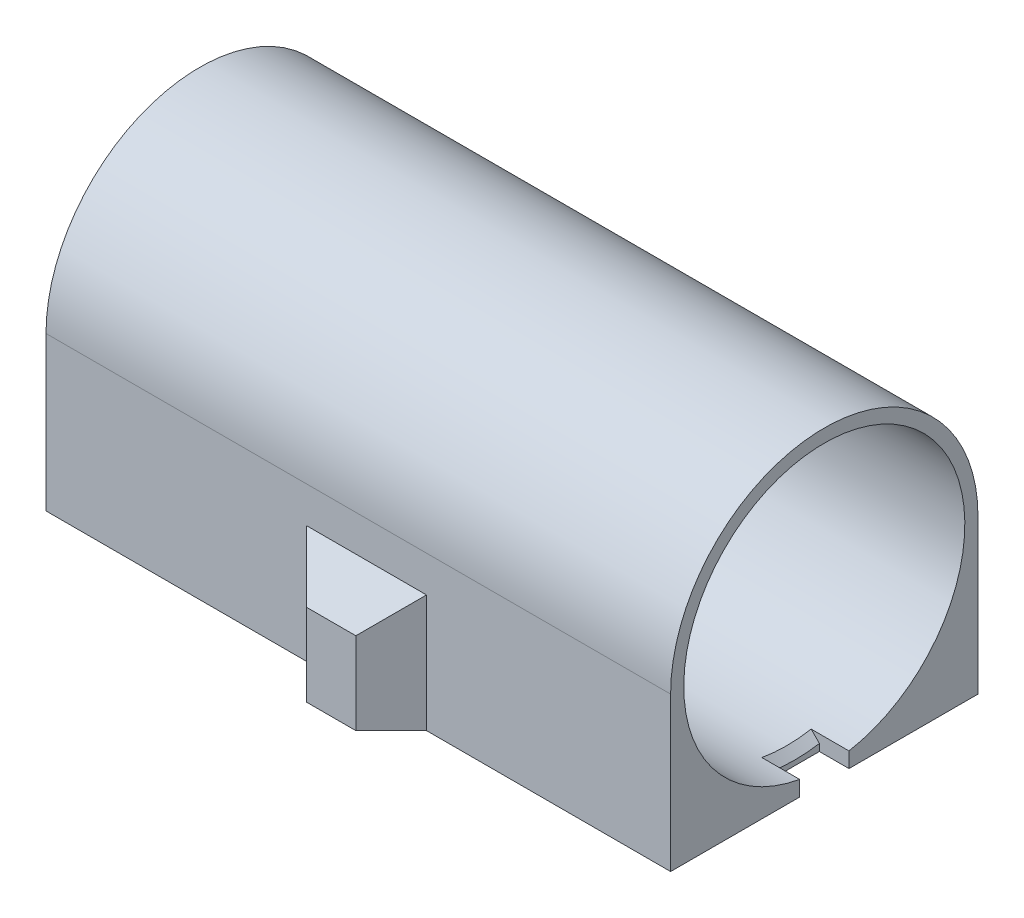
SolidWorks part; units mm, degrees
ref_plane "Спереди" through (0, 0, 0) normal (0, 0, 1) x (1, 0, 0)
ref_plane "Сверху" through (0, 0, 0) normal (0, 1, 0) x (1, 0, 0)
ref_plane "Справа" through (0, 0, 0) normal (1, 0, 0) x (0, 0, -1)
sketch "Эскиз1" plane through (0, 0, 0) normal (1, 0, 0) x (0, 0, -1)
  line L0 (-9.35, 0) -> (-9.35, -9.35)
  line L1 (-9.35, -9.35) -> (9.35, -9.35)
  line L2 (0, -1000) -> (0, 49000) construction
  line L3 (9.35, 0) -> (9.35, -9.35)
  arc A3 (9.35, 0) -> (-9.35, 0) centre (0, 0) ccw
  circle A4 centre (0, 0) radius 8.35 construction
  circle A5 centre (0, 0) radius 8.55
  arc A6 (0, -9.35) -> (9.35, 0) centre (0, 0) ccw construction
  circle A7 centre (0, 0) radius 9.35 construction
  arc A8 (-9.35, 0) -> (0, -9.35) centre (0, 0) ccw construction
  point P14 (0, -9.35)
  dimension "D1" = 0.2
  dimension "D2" = 0.8
extrude "Бобышка-Вытянуть1" add sketch "Эскиз1" along normal blind 18.5 and the other way blind 19.5
sketch "Эскиз6" plane through (-19.5, 0, 0) normal (-1, 0, 0) x (0, 0, 1)
  line L9 (-9.35, -9.35) -> (9.35, -9.35)
  line L10 (9.35, -9.35) -> (9.35, 0)
  line L11 (-9.35, 0) -> (-9.35, -9.35)
  line L16 (-9.35, -9.35) -> (9.35, -9.35)
  line L17 (9.35, -9.35) -> (9.35, 0)
  line L18 (-9.35, 0) -> (-9.35, -9.35)
  circle A0 centre (0, 0) radius 3
  arc A1 (9.35, 0) -> (-9.35, 0) centre (0, 0) ccw
  arc A2 (9.35, 0) -> (-9.35, 0) centre (0, 0) ccw
  dimension "D2" = 6
  dimension "D1" = 0
extrude "Бобышка-Вытянуть3" add sketch "Эскиз6" against normal blind 2
sketch "Эскиз2" plane through (0, -9.35, 0) normal (0, -1, 0) x (1, 0, 0)
  line L0 (-17.5, 1.5) -> (-17.5, -1.5)
  line L1 (-17.5, 1.5) -> (-22, 1.5) construction
  line L2 (-22, -1.5) -> (-17.5, -1.5) construction
  line L4 (-16.7, 1.5) -> (-22, 1.5)
  line L5 (-22, 1.5) -> (-22, -1.5)
  line L6 (-22, -1.5) -> (-16.7, -1.5)
  line L7 (-16.7, -1.5) -> (-16.7, 1.5)
  line L8 (-16.7, 1.5) -> (-17.5, 1.5)
  line L9 (-22, 1.5) -> (-22, -1.5) construction
  line L10 (-17.5, -1.5) -> (-16.7, -1.5)
  line L11 (-16.7, -1.5) -> (-16.7, 1.5)
  dimension "D2" = 0.8
  dimension "D1" = 0
extrude "Вырез-Вытянуть1" cut sketch "Эскиз2" against normal up to surface (0.9326 mm away)
sketch "Эскиз3" plane through (-19.5, 0, 0) normal (-1, 0, 0) x (0, 0, 1)
  line L4 (-1.5, -9.35) -> (1.5, -9.35)
  line L5 (1.5, -9.35) -> (1.5, -9.05)
  line L6 (1.5, -9.05) -> (-1.5, -9.05)
  line L7 (-1.5, -9.05) -> (-1.5, -9.35)
  line L8 (-1.5, -9.35) -> (1.5, -9.35)
  line L9 (1.5, -9.35) -> (1.5, -9.05)
  line L10 (1.5, -9.05) -> (-1.5, -9.05)
  line L11 (-1.5, -9.05) -> (-1.5, -9.35)
  dimension "D1" = 0
extrude "Вырез-Вытянуть2" cut sketch "Эскиз3" against normal up to surface (2 mm away) up to face at (-17.5, 0, 3)
chamfer "Фаска1" distance 0.5 angle 45 1 edges at (-16.7, -8.55, 0)
mirror "Зеркальное отражение1" about plane through (0, 0, 0) normal (1, 0, 0) of "Вырез-Вытянуть1", "Фаска1"
sketch "Эскиз7" plane through (18.5, 0, 0) normal (1, 0, 0) x (0, 0, -1)
  line L14 (1.5, -9.35) -> (1.5, -8.4174)
  line L15 (-1.5, -9.35) -> (1.5, -9.35)
  line L16 (-1.5, -8.4174) -> (-1.5, -9.35)
  line L17 (1.5, -9.35) -> (1.5, -8.4174)
  line L18 (-1.5, -9.35) -> (1.5, -9.35)
  line L19 (-1.5, -8.4174) -> (-1.5, -9.35)
  arc A1 (-1.5, -8.4174) -> (1.5, -8.4174) centre (0, 0) ccw
  arc A6 (-1.5, -8.4174) -> (1.5, -8.4174) centre (0, 0) ccw
  dimension "D1" = 0
extrude "Вырез-Вытянуть4" cut sketch "Эскиз7" against normal up to surface (1 mm away) up to face at (17.5, -8.9168, 0)
chamfer "Фаска2" distance 1 angle 45 1 edges at (-17.5, -9.05, 0)
sketch "Эскиз8" plane through (0, -9.35, 0) normal (0, -1, 0) x (1, 0, 0)
  line L0 (0, -1000) -> (0, 49000) construction
  line L1 (-1.5, 11.5) -> (1.5, 11.5)
  line L2 (1.5, 11.5) -> (3.65, 9.35)
  line L3 (-19.5, 9.35) -> (18.5, 9.35) construction
  line L4 (-3.65, 9.35) -> (3.65, 9.35)
  line L5 (1.5, 11.5) -> (1.5, 8.5) construction
  line L6 (-1.5, 11.5) -> (-3.65, 9.35)
  line L7 (3.65, 9.35) -> (18.5, 9.35) construction
  line L8 (-19.5, 9.35) -> (-3.65, 9.35) construction
  circle A0 centre (0, 8.5) radius 1.5 construction
  point P12 (0, 11.5)
  dimension "D1" = 3
  dimension "D2" = 8.5
  dimension "D3" = 45
  dimension "D4" = 3
extrude "Бобышка-Вытянуть4" add sketch "Эскиз8" against normal blind 5
sketch "Эскиз9" plane through (0, -9.35, 0) normal (0, -1, 0) x (1, 0, 0)
  circle A0 centre (0, 8.5) radius 1.5 construction
  circle A1 centre (0, 8.5) radius 1.5
extrude "Вырез-Вытянуть5" cut sketch "Эскиз9" against normal blind 4
chamfer "Фаска3" distance 0.5 angle 45 1 edges at (0, -9.35, 7)
mirror "Зеркальное отражение2" about plane through (0, 0, 0) normal (0, 0, 1) of "Фаска3", "Вырез-Вытянуть5", "Бобышка-Вытянуть4"
draft "Уклон3" type of draft neutral plane draft angle 45 faces to draft 1 face at (0, -4.35, 10.425) neutral plane through (-1.5, -4.35, 11.5) neutral plane normal (0, 0, 1) parameters "D1"=45
draft "Уклон4" type of draft neutral plane draft angle 45 faces to draft 1 face at (0, -4.35, -10.425) neutral plane through (-1.5, -4.35, -11.5) neutral plane normal (0, 0, -1) parameters "D1"=45
